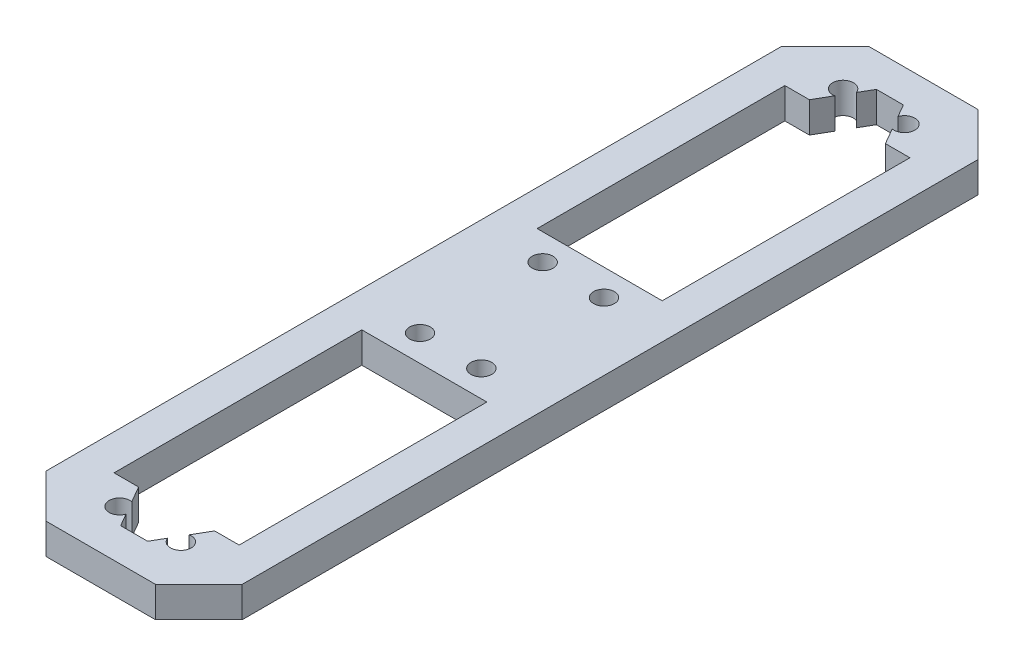
SolidWorks part; units mm, degrees
ref_plane "前视基准面" through (0, 0, 0) normal (0, 0, 1) x (1, 0, 0)
ref_plane "上视基准面" through (0, 0, 0) normal (0, 1, 0) x (1, 0, 0)
ref_plane "右视基准面" through (0, 0, 0) normal (1, 0, 0) x (0, 0, -1)
other "Configuration Table"
sketch "草图1" plane through (0, 0, 0) normal (0, 1, 0) x (1, 0, 0)
  line L0 (2576.2504, 1487.5271) -> (2555.8504, 1487.5271)
  line L1 (2555.8504, 1487.5271) -> (2555.8504, 1527.9271)
  line L2 (2576.2504, 1487.5271) -> (2576.2504, 1527.9271)
  line L3 (2555.8504, 1527.9271) -> (2559.8504, 1527.9271)
  line L4 (2559.8504, 1527.9271) -> (2561.3689, 1530.5572)
  line L5 (2562.6558, 1532.7863) -> (2563.8504, 1534.8553)
  line L6 (2576.2504, 1527.9271) -> (2572.2504, 1527.9271)
  line L7 (2572.2504, 1527.9271) -> (2570.7319, 1530.5572)
  line L8 (2569.445, 1532.7863) -> (2568.2504, 1534.8553)
  line L9 (2568.2504, 1534.8553) -> (2563.8504, 1534.8553)
  line L10 (2550.0504, 1533.2271) -> (2557.1215, 1540.2982)
  line L11 (2582.0504, 1533.2271) -> (2574.9793, 1540.2982)
  line L12 (2557.1215, 1540.2982) -> (2574.9793, 1540.2982)
  line L13 (2550.0504, 1533.2271) -> (2550.0504, 1413.2271)
  line L14 (2582.0504, 1533.2271) -> (2582.0504, 1413.2271)
  line L15 (2555.8504, 1458.9271) -> (2576.2504, 1458.9271)
  line L16 (2576.2504, 1458.9271) -> (2576.2504, 1418.5271)
  line L17 (2555.8504, 1458.9271) -> (2555.8504, 1418.5271)
  line L18 (2576.2504, 1418.5271) -> (2572.2504, 1418.5271)
  line L19 (2572.2504, 1418.5271) -> (2570.7319, 1415.897)
  line L20 (2569.445, 1413.668) -> (2568.2504, 1411.5989)
  line L21 (2555.8504, 1418.5271) -> (2559.8504, 1418.5271)
  line L22 (2559.8504, 1418.5271) -> (2561.3689, 1415.897)
  line L23 (2562.6558, 1413.668) -> (2563.8504, 1411.5989)
  line L24 (2563.8504, 1411.5989) -> (2568.2504, 1411.5989)
  line L25 (2582.0504, 1413.2271) -> (2574.9793, 1406.1561)
  line L26 (2550.0504, 1413.2271) -> (2557.1215, 1406.1561)
  line L27 (2574.9793, 1406.1561) -> (2557.1215, 1406.1561)
  arc A0 (2570.7319, 1530.5572) -> (2569.445, 1532.7863) centre (2571.0504, 1532.2271) ccw
  arc A1 (2562.6558, 1532.7863) -> (2561.3689, 1530.5572) centre (2561.0504, 1532.2271) ccw
  circle A2 centre (2571.0504, 1483.2271) radius 1.7
  circle A3 centre (2561.0504, 1483.2271) radius 1.7
  arc A4 (2561.3689, 1415.897) -> (2562.6558, 1413.668) centre (2561.0504, 1414.2271) ccw
  arc A5 (2569.445, 1413.668) -> (2570.7319, 1415.897) centre (2571.0504, 1414.2271) ccw
  circle A6 centre (2561.0504, 1463.2271) radius 1.7
  circle A7 centre (2571.0504, 1463.2271) radius 1.7
extrude "凸台-拉伸1" add sketch "草图1" along normal blind 5
